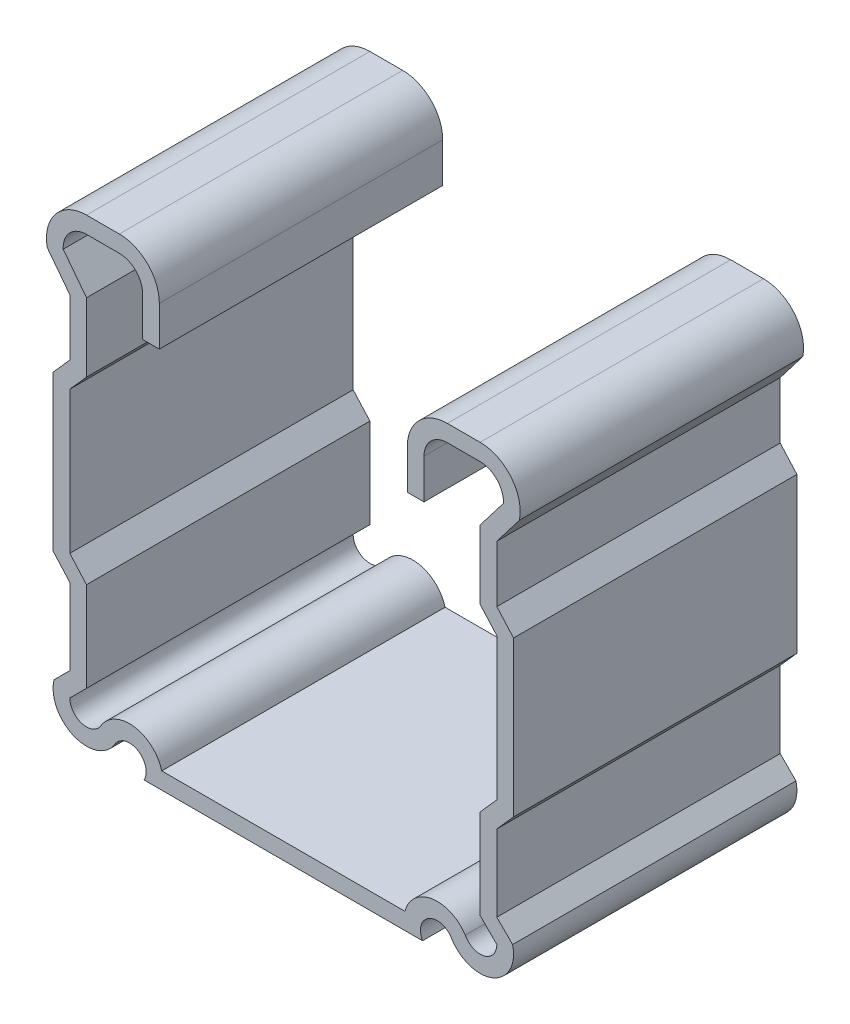
SolidWorks part; units mm, degrees
ref_plane "Plane1" through (0, 0, 0) normal (0, 0, 1) x (1, 0, 0)
ref_plane "Plane2" through (0, 0, 0) normal (0, 1, 0) x (1, 0, 0)
ref_plane "Plane3" through (0, 0, 0) normal (1, 0, 0) x (0, 0, -1)
sketch "Sketch1" plane through (0, 0, 0) normal (0, 0, 1) x (1, 0, 0)
  line L0 (17.6403, 16.3393) -> (19.7299, 19.0635)
  line L1 (17.6403, -13.9795) -> (19.1389, -15.4781)
  line L2 (-17.6403, -13.9795) -> (-19.1389, -15.4781)
  line L4 (-17.6403, -13.9795) -> (-17.6403, -5.9368)
  line L5 (17.6403, 21.2598) -> (14.7033, 21.2598)
  line L6 (12.6111, 19.1676) -> (12.6111, 15.6147)
  line L7 (-17.6403, -5.9368) -> (-19.1389, -4.2539)
  line L8 (-12.6111, 19.1676) -> (-12.6111, 15.6147)
  line L9 (0, 10.16) -> (0, -7.62) construction
  line L10 (-19.1389, -4.2539) -> (-19.1389, 8.4957)
  line L11 (-17.6403, 10.1786) -> (-19.1389, 8.4957)
  line L12 (-17.6403, 10.1786) -> (-17.6403, 16.3393)
  line L13 (-17.6403, 16.3393) -> (-19.7299, 19.0635)
  line L14 (-17.6403, 21.2598) -> (-14.7033, 21.2598)
  line L16 (17.6403, -13.9795) -> (17.6403, -5.9368)
  line L17 (17.6403, 10.1786) -> (17.6403, 16.3393)
  line L18 (-11.1125, 19.1676) -> (-11.1125, 15.6147)
  line L19 (-17.6403, 22.7584) -> (-14.7033, 22.7584)
  line L20 (-19.1389, 15.8307) -> (-21.1624, 18.4689)
  line L21 (-19.1389, 10.7491) -> (-19.1389, 15.8307)
  line L22 (-19.1389, 10.7491) -> (-20.6375, 9.0662)
  line L23 (-20.6375, -4.8244) -> (-20.6375, 9.0662)
  line L24 (-19.1389, -6.5073) -> (-20.6375, -4.8244)
  line L25 (19.1389, -4.2539) -> (19.1389, 8.4957)
  line L26 (-19.1389, -13.3588) -> (-19.1389, -6.5073)
  line L27 (-19.1389, -13.3588) -> (-20.5535, -14.7733)
  line L28 (11.1125, 19.1676) -> (11.1125, 15.6147)
  line L29 (17.6403, 22.7584) -> (14.7033, 22.7584)
  line L30 (19.1389, 15.8307) -> (21.1624, 18.4689)
  line L31 (19.1389, 10.7491) -> (19.1389, 15.8307)
  line L32 (19.1389, 10.7491) -> (20.6375, 9.0662)
  line L33 (20.6375, -4.8244) -> (20.6375, 9.0662)
  line L34 (19.1389, -6.5073) -> (20.6375, -4.8244)
  line L35 (19.1389, -13.3588) -> (19.1389, -6.5073)
  line L36 (19.1389, -13.3588) -> (20.5535, -14.7733)
  line L37 (17.6403, -5.9368) -> (19.1389, -4.2539)
  line L38 (-12.4806, -18.5166) -> (12.4806, -18.5166)
  line L39 (17.6403, 10.1786) -> (19.1389, 8.4957)
  line L41 (-10.899, -17.018) -> (10.899, -17.018)
  line L42 (-12.6111, 15.6147) -> (-11.1125, 15.6147)
  line L43 (11.1125, 15.6147) -> (12.6111, 15.6147)
  arc A0 (19.1389, -15.4781) -> (16.3052, -16.1588) centre (17.6403, -15.4781) cw
  arc A1 (16.3052, -16.1588) -> (10.899, -17.018) centre (13.7938, -17.7947) ccw
  arc A2 (-16.4143, -16.3399) -> (-10.899, -17.018) centre (-13.7938, -17.7947) cw
  arc A3 (-19.1389, -15.4781) -> (-16.4143, -16.3399) centre (-17.6403, -15.4781) ccw
  arc A4 (-17.6403, 21.2598) -> (-19.7299, 19.0635) centre (-17.6403, 19.1676) ccw
  arc A5 (-12.6111, 19.1676) -> (-14.7033, 21.2598) centre (-14.7033, 19.1676) ccw
  arc A6 (17.6403, 21.2598) -> (19.7299, 19.0635) centre (17.6403, 19.1676) cw
  arc A7 (12.6111, 19.1676) -> (14.7033, 21.2598) centre (14.7033, 19.1676) cw
  arc A8 (-11.1125, 19.1676) -> (-14.7033, 22.7584) centre (-14.7033, 19.1676) ccw
  arc A9 (-17.6403, 22.7584) -> (-21.1624, 18.4689) centre (-17.6403, 19.1676) ccw
  arc A10 (-20.5535, -14.7733) -> (-15.0198, -16.9329) centre (-17.6403, -15.4781) ccw
  arc A11 (11.1125, 19.1676) -> (14.7033, 22.7584) centre (14.7033, 19.1676) cw
  arc A12 (17.6403, 22.7584) -> (21.1624, 18.4689) centre (17.6403, 19.1676) cw
  arc A13 (20.5535, -14.7733) -> (15.0198, -16.9329) centre (17.6403, -15.4781) cw
  arc A14 (15.0198, -16.9329) -> (12.4806, -18.5166) centre (13.7938, -17.7947) ccw
  arc A15 (-15.0198, -16.9329) -> (-12.4806, -18.5166) centre (-13.7938, -17.7947) cw
  dimension "D9" = 7.1437
  dimension "base" = 18.5166
  dimension "D5" = 9.525
  dimension "ToeHt" = 22.7584
  dimension "D6" = 22.225
  dimension "D8" = 15.4781
  dimension "D12" = 41.275
  dimension "D14" = 13.6922
  dimension "D15" = 13.8906
extrude "Base-Extrude" add sketch "Sketch1" along normal mid plane 25.4
